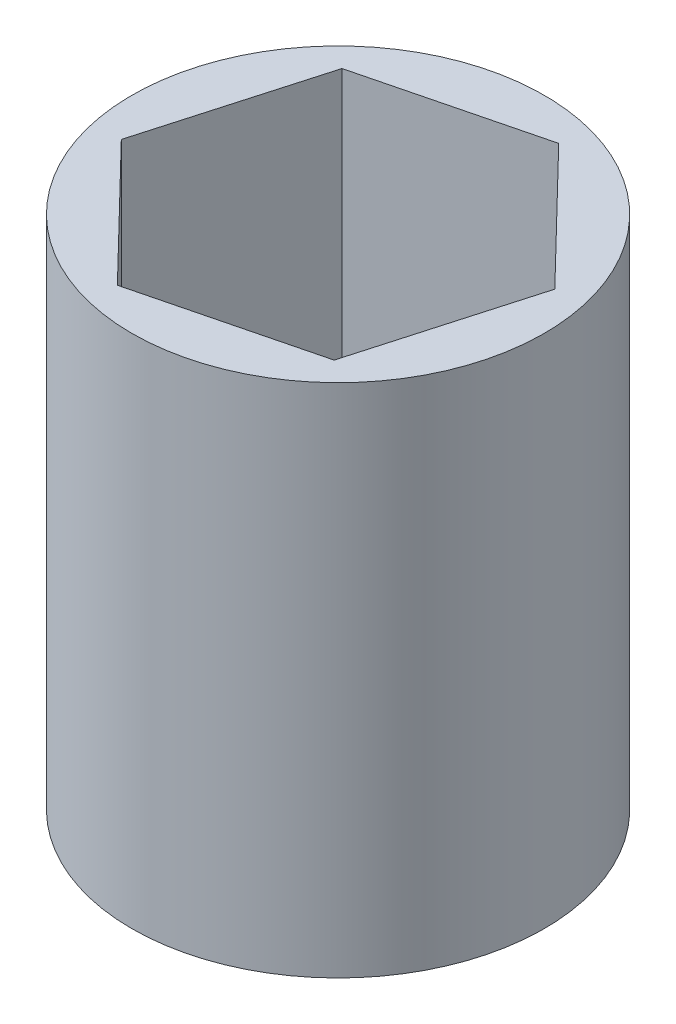
SolidWorks part; units mm, degrees
ref_plane "Front Plane" through (0, 0, 0) normal (0, 0, 1) x (1, 0, 0)
ref_plane "Top Plane" through (0, 0, 0) normal (0, 1, 0) x (1, 0, 0)
ref_plane "Right Plane" through (0, 0, 0) normal (1, 0, 0) x (0, 0, -1)
sketch "Sketch1" plane through (0, 0, 0) normal (0, 1, 0) x (1, 0, 0)
  line L1 (1.5057, 5.2891) -> (-3.8277, 3.9485)
  line L2 (-3.8277, 3.9485) -> (-5.3333, -1.3406)
  line L3 (-5.3333, -1.3406) -> (-1.5057, -5.2891)
  line L4 (-1.5057, -5.2891) -> (3.8277, -3.9485)
  line L5 (3.8277, -3.9485) -> (5.3333, 1.3406)
  line L6 (5.3333, 1.3406) -> (1.5057, 5.2891)
  circle A0 centre (0, 0) radius 4.7625 construction
  circle A1 centre (0, 0) radius 6.35
  dimension "D2" = 12.7
  dimension "D1" = 9.525
extrude "Boss-Extrude1" add sketch "Sketch1" along normal blind 15.875
